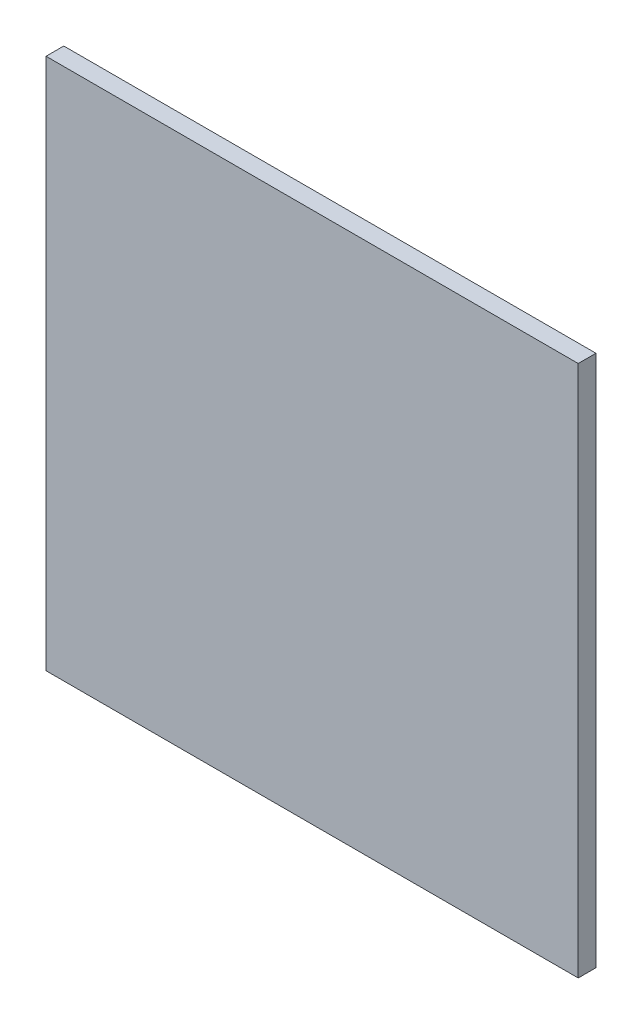
SolidWorks part; units mm, degrees
ref_plane "Front Plane" through (0, 0, 0) normal (0, 0, 1) x (1, 0, 0)
ref_plane "Top Plane" through (0, 0, 0) normal (0, 1, 0) x (1, 0, 0)
ref_plane "Right Plane" through (0, 0, 0) normal (1, 0, 0) x (0, 0, -1)
sketch "Sketch1" plane through (0, 0, 0) normal (0, 0, 1) x (1, 0, 0)
  line L1 (-1500, 1500) -> (1500, 1500)
  line L2 (-1500, 1500) -> (-1500, -1500)
  line L3 (-1500, -1500) -> (1500, -1500)
  line L4 (1500, 1500) -> (1500, -1500)
  line L5 (-1500, 1500) -> (1500, -1500) construction
  line L6 (-1500, -1500) -> (1500, 1500) construction
  point P0 (0, 0)
  dimension "D1" = 3000
  dimension "D2" = 3000
extrude "Boss-Extrude1" add sketch "Sketch1" against normal blind 100
